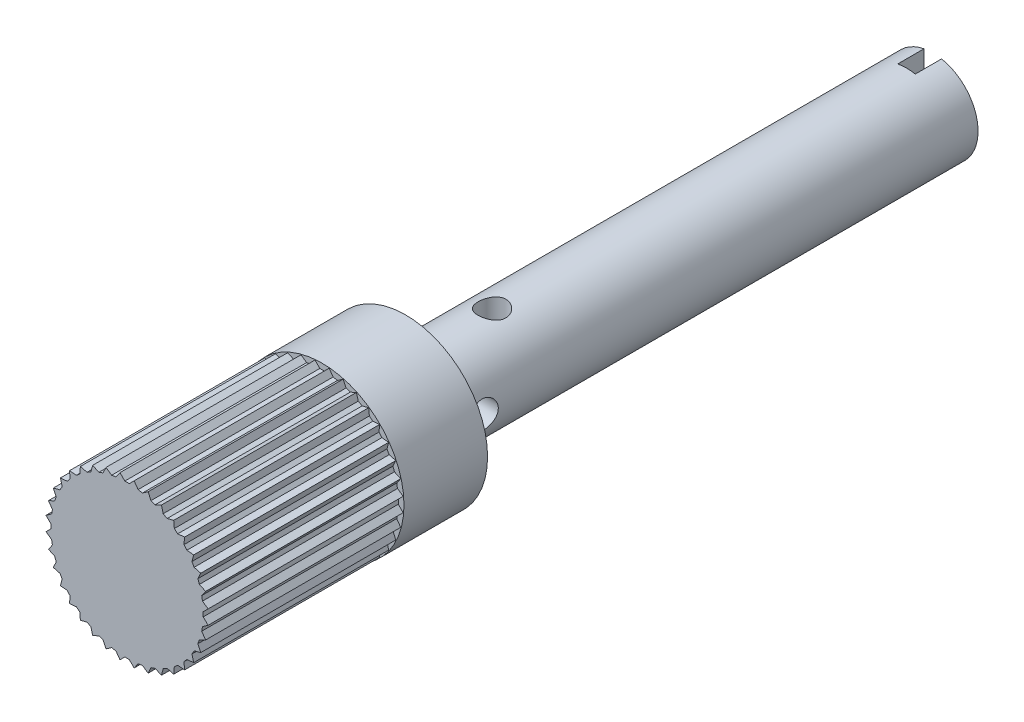
SolidWorks part; units mm, degrees
material "AISI 4130 Steel, annealed at 865C"
ref_plane "X-Y Datum" through (0, 0, 0) normal (0, 0, 1) x (1, 0, 0)
ref_plane "X-Z Datum" through (0, 0, 0) normal (0, 1, 0) x (1, 0, 0)
ref_plane "Y-Z Datum" through (0, 0, 0) normal (1, 0, 0) x (0, 0, -1)
sketch "Sketch9" plane through (0, 0, 0) normal (0, 1, 0) x (1, 0, 0)
  line L0 (16.002, 0) -> (0, 0)
  line L1 (0, 0) -> (0, -382.27)
  line L2 (0, -382.27) -> (-72.2493, -518.1512)
  dimension "D1" = 153.895
  dimension "D2" = 28
  dimension "D3" = 382.27
  dimension "D5" = 16.002
sketch "Sketch5" plane through (0, 0, 0) normal (0, 1, 0) x (1, 0, 0)
  line L0 (0, 0) -> (0, -60.071)
  line L1 (0, -60.071) -> (5.1587, -60.071)
  line L2 (5.1587, -60.071) -> (5.1587, 0)
  line L3 (5.1587, 0) -> (0, 0)
  dimension "D1" = 60.071
  dimension "D2" = 5.1587
revolve "Revolve2" add sketch "Sketch5" angle 360 about L1
sketch "Sketch10" plane through (0, 0, 60.071) normal (0, 0, 1) x (1, 0, 0)
  circle A0 centre (0, 0) radius 9.3345
  dimension "D1" = 18.669
extrude "Boss-Extrude1" add sketch "Sketch10" along normal blind 31.75
sketch "Sketch8" plane through (0, 0, 0) normal (0, 0, 1) x (1, 0, 0)
  line L0 (9.2357, -0.808) -> (8.6817, -0.254)
  line L1 (8.6817, -0.254) -> (8.6817, 0.254)
  line L2 (8.6817, 0.254) -> (9.2357, 0.808)
  line L3 (8.6817, 0) -> (0, 0) construction
  line L4 (8.9551, -2.3995) -> (8.5057, -1.7577)
  line L5 (8.5057, -1.7577) -> (8.5939, -1.2574)
  line L6 (8.5939, -1.2574) -> (9.2357, -0.808)
  line L7 (8.4024, -3.9181) -> (8.0713, -3.208)
  line L8 (8.0713, -3.208) -> (8.245, -2.7306)
  line L9 (8.245, -2.7306) -> (8.9551, -2.3995)
  line L10 (7.5944, -5.3176) -> (7.3916, -4.5608)
  line L11 (7.3916, -4.5608) -> (7.6456, -4.1209)
  line L12 (7.6456, -4.1209) -> (8.4024, -3.9181)
  line L13 (6.5556, -6.5556) -> (6.4873, -5.7751)
  line L14 (6.4873, -5.7751) -> (6.8138, -5.3859)
  line L15 (6.8138, -5.3859) -> (7.5944, -5.3176)
  line L16 (5.3176, -7.5944) -> (5.3859, -6.8138)
  line L17 (5.3859, -6.8138) -> (5.7751, -6.4873)
  line L18 (5.7751, -6.4873) -> (6.5556, -6.5556)
  line L19 (3.9181, -8.4024) -> (4.1209, -7.6456)
  line L20 (4.1209, -7.6456) -> (4.5608, -7.3916)
  line L21 (4.5608, -7.3916) -> (5.3176, -7.5944)
  line L22 (2.3995, -8.9551) -> (2.7306, -8.245)
  line L23 (2.7306, -8.245) -> (3.208, -8.0713)
  line L24 (3.208, -8.0713) -> (3.9181, -8.4024)
  line L25 (0.808, -9.2357) -> (1.2574, -8.5939)
  line L26 (1.2574, -8.5939) -> (1.7577, -8.5057)
  line L27 (1.7577, -8.5057) -> (2.3995, -8.9551)
  line L28 (-0.808, -9.2357) -> (-0.254, -8.6817)
  line L29 (-0.254, -8.6817) -> (0.254, -8.6817)
  line L30 (0.254, -8.6817) -> (0.808, -9.2357)
  line L31 (-2.3995, -8.9551) -> (-1.7577, -8.5057)
  line L32 (-1.7577, -8.5057) -> (-1.2574, -8.5939)
  line L33 (-1.2574, -8.5939) -> (-0.808, -9.2357)
  line L34 (-3.9181, -8.4024) -> (-3.208, -8.0713)
  line L35 (-3.208, -8.0713) -> (-2.7306, -8.245)
  line L36 (-2.7306, -8.245) -> (-2.3995, -8.9551)
  line L37 (-5.3176, -7.5944) -> (-4.5608, -7.3916)
  line L38 (-4.5608, -7.3916) -> (-4.1209, -7.6456)
  line L39 (-4.1209, -7.6456) -> (-3.9181, -8.4024)
  line L40 (-6.5556, -6.5556) -> (-5.7751, -6.4873)
  line L41 (-5.7751, -6.4873) -> (-5.3859, -6.8138)
  line L42 (-5.3859, -6.8138) -> (-5.3176, -7.5944)
  line L43 (-7.5944, -5.3176) -> (-6.8138, -5.3859)
  line L44 (-6.8138, -5.3859) -> (-6.4873, -5.7751)
  line L45 (-6.4873, -5.7751) -> (-6.5556, -6.5556)
  line L46 (-8.4024, -3.9181) -> (-7.6456, -4.1209)
  line L47 (-7.6456, -4.1209) -> (-7.3916, -4.5608)
  line L48 (-7.3916, -4.5608) -> (-7.5944, -5.3176)
  line L49 (-8.9551, -2.3995) -> (-8.245, -2.7306)
  line L50 (-8.245, -2.7306) -> (-8.0713, -3.208)
  line L51 (-8.0713, -3.208) -> (-8.4024, -3.9181)
  line L52 (-9.2357, -0.808) -> (-8.5939, -1.2574)
  line L53 (-8.5939, -1.2574) -> (-8.5057, -1.7577)
  line L54 (-8.5057, -1.7577) -> (-8.9551, -2.3995)
  line L55 (-9.2357, 0.808) -> (-8.6817, 0.254)
  line L56 (-8.6817, 0.254) -> (-8.6817, -0.254)
  line L57 (-8.6817, -0.254) -> (-9.2357, -0.808)
  line L58 (-8.9551, 2.3995) -> (-8.5057, 1.7577)
  line L59 (-8.5057, 1.7577) -> (-8.5939, 1.2574)
  line L60 (-8.5939, 1.2574) -> (-9.2357, 0.808)
  line L61 (-8.4024, 3.9181) -> (-8.0713, 3.208)
  line L62 (-8.0713, 3.208) -> (-8.245, 2.7306)
  line L63 (-8.245, 2.7306) -> (-8.9551, 2.3995)
  line L64 (-7.5944, 5.3176) -> (-7.3916, 4.5608)
  line L65 (-7.3916, 4.5608) -> (-7.6456, 4.1209)
  line L66 (-7.6456, 4.1209) -> (-8.4024, 3.9181)
  line L67 (-6.5556, 6.5556) -> (-6.4873, 5.7751)
  line L68 (-6.4873, 5.7751) -> (-6.8138, 5.3859)
  line L69 (-6.8138, 5.3859) -> (-7.5944, 5.3176)
  line L70 (-5.3176, 7.5944) -> (-5.3859, 6.8138)
  line L71 (-5.3859, 6.8138) -> (-5.7751, 6.4873)
  line L72 (-5.7751, 6.4873) -> (-6.5556, 6.5556)
  line L73 (-3.9181, 8.4024) -> (-4.1209, 7.6456)
  line L74 (-4.1209, 7.6456) -> (-4.5608, 7.3916)
  line L75 (-4.5608, 7.3916) -> (-5.3176, 7.5944)
  line L76 (-2.3995, 8.9551) -> (-2.7306, 8.245)
  line L77 (-2.7306, 8.245) -> (-3.208, 8.0713)
  line L78 (-3.208, 8.0713) -> (-3.9181, 8.4024)
  line L79 (-0.808, 9.2357) -> (-1.2574, 8.5939)
  line L80 (-1.2574, 8.5939) -> (-1.7577, 8.5057)
  line L81 (-1.7577, 8.5057) -> (-2.3995, 8.9551)
  line L82 (0.808, 9.2357) -> (0.254, 8.6817)
  line L83 (0.254, 8.6817) -> (-0.254, 8.6817)
  line L84 (-0.254, 8.6817) -> (-0.808, 9.2357)
  line L85 (2.3995, 8.9551) -> (1.7577, 8.5057)
  line L86 (1.7577, 8.5057) -> (1.2574, 8.5939)
  line L87 (1.2574, 8.5939) -> (0.808, 9.2357)
  line L88 (3.9181, 8.4024) -> (3.208, 8.0713)
  line L89 (3.208, 8.0713) -> (2.7306, 8.245)
  line L90 (2.7306, 8.245) -> (2.3995, 8.9551)
  line L91 (5.3176, 7.5944) -> (4.5608, 7.3916)
  line L92 (4.5608, 7.3916) -> (4.1209, 7.6456)
  line L93 (4.1209, 7.6456) -> (3.9181, 8.4024)
  line L94 (6.5556, 6.5556) -> (5.7751, 6.4873)
  line L95 (5.7751, 6.4873) -> (5.3859, 6.8138)
  line L96 (5.3859, 6.8138) -> (5.3176, 7.5944)
  line L97 (7.5944, 5.3176) -> (6.8138, 5.3859)
  line L98 (6.8138, 5.3859) -> (6.4873, 5.7751)
  line L99 (6.4873, 5.7751) -> (6.5556, 6.5556)
  line L100 (8.4024, 3.9181) -> (7.6456, 4.1209)
  line L101 (7.6456, 4.1209) -> (7.3916, 4.5608)
  line L102 (7.3916, 4.5608) -> (7.5944, 5.3176)
  line L103 (8.9551, 2.3995) -> (8.245, 2.7306)
  line L104 (8.245, 2.7306) -> (8.0713, 3.208)
  line L105 (8.0713, 3.208) -> (8.4024, 3.9181)
  line L106 (9.2357, 0.808) -> (8.5939, 1.2574)
  line L107 (8.5939, 1.2574) -> (8.5057, 1.7577)
  line L108 (8.5057, 1.7577) -> (8.9551, 2.3995)
  circle A0 centre (0, 0) radius 12.7
  circle A1 centre (0, 0) radius 9.271 construction
  circle A2 centre (0, 0) radius 8.6854 construction
  point P153 (0, 0)
  dimension "D1" = 25.4
  dimension "D4" = 18.542
  dimension "D6" = 17.3708
  dimension "D2" = 0.508
  dimension "D3" = 135
  dimension "D5" = 36
extrude "Cut-Extrude7" cut sketch "Sketch8" against normal blind 22.225 from surface at 91.821 starting at face at (9.3345, 0, 91.821)
sketch "Sketch11" plane through (0, 0, 0) normal (0, 1, 0) x (1, 0, 0)
  line L0 (5.1587, 0) -> (-5.1587, 0) construction
  line L1 (-1, 0) -> (1, 0)
  line L2 (-1, 0) -> (-1, -3)
  line L3 (-1, -3) -> (1, -3)
  line L4 (1, 0) -> (1, -3)
  point P6 (0, 0)
  dimension "D1" = 2
  dimension "D2" = 3
extrude "Cut-Extrude9" cut sketch "Sketch11" along normal through all both and the other way through all
sketch "Sketch12" plane through (0, 0, 0) normal (0, 1, 0) x (1, 0, 0)
  line L0 (9.3345, -60.071) -> (-9.3345, -60.071) construction
  circle A0 centre (0, -50.2285) radius 1.5875
  dimension "D1" = 9.8425
  dimension "D2" = 3.175
extrude "Cut-Extrude10" cut sketch "Sketch12" against normal through all both and the other way through all
sketch "Sketch13" plane through (0, 0, 0) normal (1, 0, 0) x (0, 0, -1)
  line L0 (-60.071, -9.3345) -> (-60.071, 9.3345) construction
  circle A0 centre (-56.261, 0) radius 1.5875
  dimension "D1" = 3.175
  dimension "D2" = 3.81
extrude "Cut-Extrude11" cut sketch "Sketch13" against normal through all both and the other way through all
